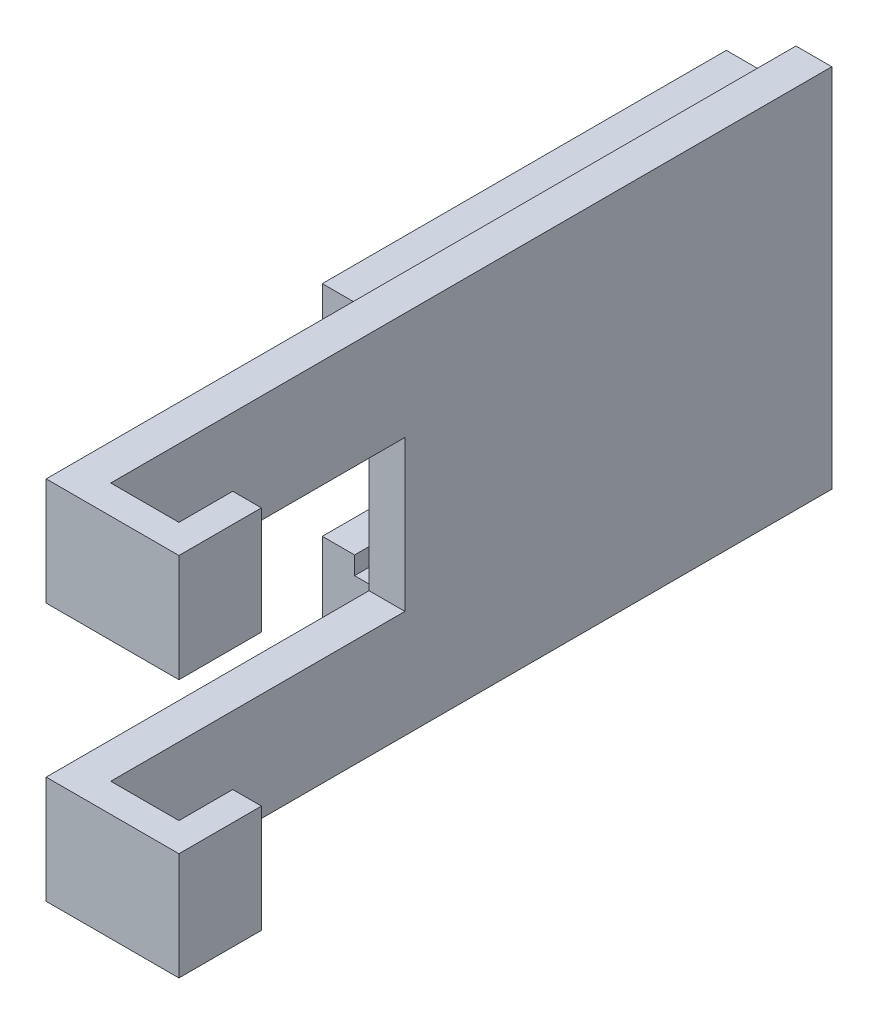
SolidWorks part; units mm, degrees
ref_plane "Front Plane" through (0, 0, 0) normal (0, 0, 1) x (1, 0, 0)
ref_plane "Top Plane" through (0, 0, 0) normal (0, 1, 0) x (1, 0, 0)
ref_plane "Right Plane" through (0, 0, 0) normal (1, 0, 0) x (0, 0, -1)
sketch "Sketch4" plane through (0, 0, 0) normal (1, 0, 0) x (0, 0, -1)
  line L0 (-200.3527, 28.0794) -> (-200.3527, -22.9206) construction
  line L1 (-252.6027, -7.9206) -> (-148.1027, -7.9206)
  line L2 (-252.6027, -7.9206) -> (-252.6027, -22.9206)
  line L3 (-252.6027, -22.9206) -> (-148.1027, -22.9206)
  line L4 (-148.1027, -7.9206) -> (-148.1027, -22.9206)
  line L5 (-252.6027, 13.0794) -> (-148.1027, 13.0794)
  line L6 (-252.6027, 13.0794) -> (-252.6027, 28.0794)
  line L7 (-252.6027, 28.0794) -> (-148.1027, 28.0794)
  line L8 (-148.1027, 13.0794) -> (-148.1027, 28.0794)
  line L9 (-161.0802, 13.0794) -> (-141.0802, 13.0794)
  line L11 (-161.0802, -7.9206) -> (-141.0802, -7.9206)
  line L13 (-200.3527, 64.3294) -> (-200.3527, -59.1706) construction
  line L14 (-252.6027, 64.3294) -> (-148.1027, 64.3294) construction
  line L15 (-252.6027, 64.3294) -> (-252.6027, -59.1706) construction
  line L16 (-252.6027, -59.1706) -> (-148.1027, -59.1706) construction
  line L17 (-148.1027, 64.3294) -> (-148.1027, -59.1706) construction
  line L18 (-252.6027, 2.5794) -> (-148.1027, 2.5794) construction
  line L19 (-213.3302, 2.5794) -> (-193.3302, 2.5794) construction
  line L24 (-148.1027, 13.0794) -> (-148.1027, -1.8845)
  line L27 (-207.6027, 13.0794) -> (-148.1027, 13.0794)
  line L28 (-207.6027, 13.0794) -> (-207.6027, -7.9206)
  line L29 (-207.6027, -7.9206) -> (-148.1027, -7.9206)
  line L30 (-148.1027, 13.0794) -> (-148.1027, -7.9206)
  point P22 (-207.6027, 2.5794)
  point P25 (0, 0)
  dimension "D1" = 21
  dimension "D2" = 15
  dimension "D3" = 15
  dimension "D4" = 123.5
  dimension "D5" = 104.5
  dimension "D6" = 45
extrude "Boss-Extrude1" add sketch "Sketch4" along normal blind 5
sketch "Sketch5" plane through (5, 0, 0) normal (1, 0, 0) x (0, 0, -1)
  line L0 (-252.6027, 13.0794) -> (-207.6027, 13.0794) construction
  line L1 (-252.6027, 28.0794) -> (-248.6027, 28.0794)
  line L2 (-252.6027, 28.0794) -> (-252.6027, 13.0794)
  line L3 (-252.6027, 13.0794) -> (-248.6027, 13.0794)
  line L4 (-248.6027, 28.0794) -> (-248.6027, 13.0794)
  line L5 (-252.6027, -22.9206) -> (-148.1027, -22.9206) construction
  line L8 (-252.6027, -7.9206) -> (-248.6027, -7.9206)
  line L11 (-252.6027, -7.9206) -> (-252.6027, -22.9206)
  line L14 (-252.6027, -22.9206) -> (-248.6027, -22.9206)
  line L15 (-248.6027, -7.9206) -> (-248.6027, -22.9206)
  line M5 (-252.6027, 13.0794) -> (-207.6027, 13.0794)
  line M15 (-148.1027, 28.0794) -> (-252.6027, 28.0794)
  line M16 (-252.6027, 28.0794) -> (-252.6027, 13.0794)
  dimension "D2" = 4
extrude "Boss-Extrude2" add sketch "Sketch5" along normal blind 13.5 contours L4 M15 M16 M5 | L11 L14 L15 L8
sketch "Sketch6" plane through (0, 0, 248.6027) normal (0, 0, -1) x (-1, 0, 0)
  line L0 (-18.5, -7.9206) -> (-5, -7.9206) construction
  line L1 (-18.5, -22.9206) -> (-14.5, -22.9206)
  line L2 (-18.5, -22.9206) -> (-18.5, -7.9206)
  line L3 (-18.5, -7.9206) -> (-14.5, -7.9206)
  line L4 (-14.5, -22.9206) -> (-14.5, -7.9206)
  line L5 (-18.5, 28.0794) -> (-5, 28.0794) construction
  line L6 (-18.5, 13.0794) -> (-14.5, 13.0794)
  line L7 (-18.5, 13.0794) -> (-18.5, 28.0794)
  line L8 (-18.5, 28.0794) -> (-14.5, 28.0794)
  line L9 (-14.5, 13.0794) -> (-14.5, 28.0794)
  dimension "D2" = 4
extrude "Boss-Extrude3" add sketch "Sketch6" along normal blind 7.5
sketch "Sketch7" plane through (0, 0, 0) normal (-1, 0, 0) x (0, 0, 1)
  line L0 (148.1027, -22.9206) -> (148.1027, 28.0794) construction
  line L1 (252.6027, 13.0794) -> (252.6027, 28.0794) construction
  line L2 (204.4196, 20.2044) -> (148.1027, 20.2044)
  line L3 (252.6027, -7.9206) -> (252.6027, -22.9206) construction
  line L4 (252.6027, 20.5794) -> (252.6027, -15.4206) construction
  line L5 (252.6027, 2.5794) -> (226.9378, 2.5794) construction
  line L6 (244.1742, 17.8294) -> (252.6027, 17.8294) construction
  line L7 (239.8065, -12.6706) -> (252.6027, -12.6706) construction
  line L8 (204.4196, 20.2044) -> (204.4196, 15.4544)
  line L9 (204.4196, 15.4544) -> (148.1027, 15.4544)
  line L10 (148.1027, 20.2044) -> (148.1027, 15.4544)
  point P5 (252.6027, 20.5794)
  point P10 (252.6027, -15.4206)
  dimension "D1" = 30.5
  dimension "D2" = 4.75
extrude "Boss-Extrude4" add sketch "Sketch7" along normal blind 5.2
sketch "Sketch8" plane through (-5.2, 0, 0) normal (-1, 0, 0) x (0, 0, 1)
  line L0 (204.4196, 17.8294) -> (148.1027, 17.8294) construction
  line L1 (204.4196, 22.7044) -> (148.1027, 22.7044)
  line L2 (204.4196, 22.7044) -> (204.4196, 12.9544)
  line L3 (204.4196, 12.9544) -> (148.1027, 12.9544)
  line L4 (148.1027, 22.7044) -> (148.1027, 12.9544)
  line L5 (204.4196, 15.4544) -> (204.4196, 20.2044) construction
  line L6 (148.1027, 20.2044) -> (148.1027, 15.4544) construction
  dimension "D1" = 9.75
extrude "Boss-Extrude5" add sketch "Sketch8" along normal blind 4.5
ref_plane "Plane1" through (0, 2.5794, 0) normal (0, -1, 0) x (-1, 0, 0)
mirror "Mirror1" about plane through (0, 2.5794, 0) normal (0, -1, 0) of "Boss-Extrude5", "Boss-Extrude4"
